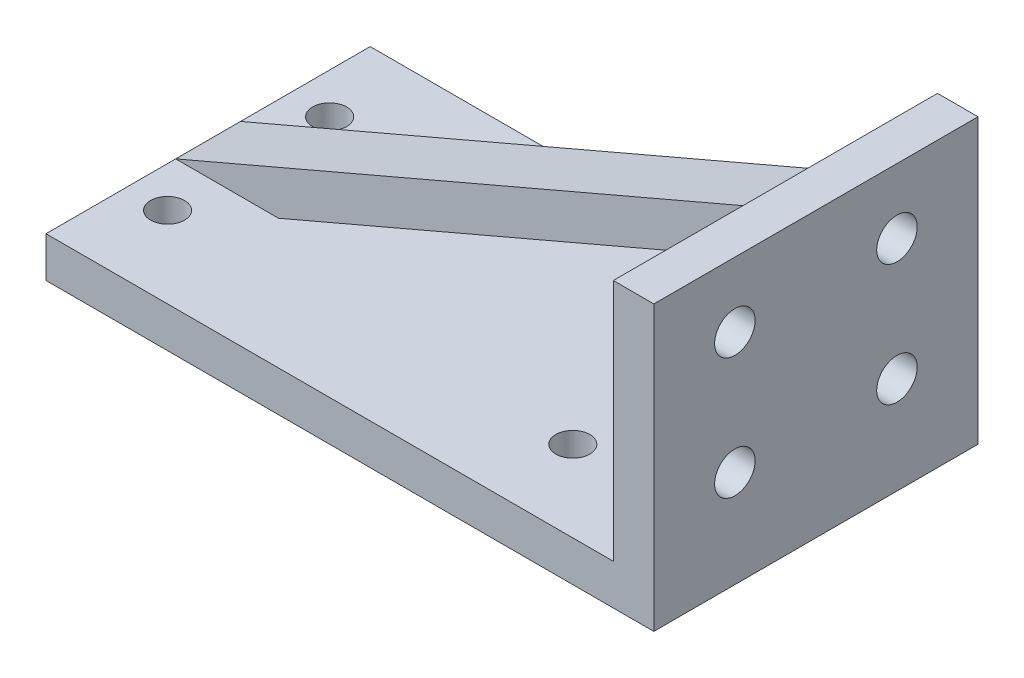
SolidWorks part; units mm, degrees
ref_plane "Front Plane" through (0, 0, 0) normal (0, 0, 1) x (1, 0, 0)
ref_plane "Top Plane" through (0, 0, 0) normal (0, 1, 0) x (1, 0, 0)
ref_plane "Right Plane" through (0, 0, 0) normal (1, 0, 0) x (0, 0, -1)
sketch "Sketch3" plane through (0, 0, 0) normal (0, 0, 1) x (1, 0, 0)
  line L0 (0, 6.35) -> (88.9, 44.45)
  line L1 (0, 0) -> (95.25, 0)
  line L2 (0, 0) -> (0, 6.35)
  line L3 (16.1201, 6.35) -> (88.9, 6.35)
  line L4 (95.25, 0) -> (95.25, 6.35)
  line L5 (95.25, 0) -> (88.9, 0)
  line L6 (95.25, 0) -> (95.25, 44.45)
  line L7 (95.25, 44.45) -> (88.9, 44.45)
  line L8 (88.9, 6.35) -> (88.9, 37.5414)
  line L9 (16.1201, 6.35) -> (88.9, 37.5414)
  line L10 (2.5014, 0.5134) -> (91.4014, 38.6134) construction
  dimension "D1" = 6.35
  dimension "D2" = 95.25
  dimension "D3" = 6.35
  dimension "D4" = 44.45
  dimension "D5" = 88.9
  dimension "D6" = 6.35
  dimension "D7" = 156.801
  dimension "D8" = 6.35
extrude "Boss-Extrude1" add sketch "Sketch3" along normal blind 50.8 contours L8 L3 L2 L1 L4 L6 L7
sketch "Sketch4" plane through (0, 0, 0) normal (0, -1, 0) x (1, 0, 0)
  line L0 (0, 50.8) -> (0, 0) construction
  line L1 (0, 0) -> (95.25, 0) construction
  line L2 (0, 50.8) -> (95.25, 50.8) construction
  circle A0 centre (6.35, 38.1) radius 2.667
  circle A1 centre (6.35, 12.7) radius 2.667
  circle A2 centre (69.85, 12.7) radius 2.667
  circle A3 centre (69.85, 38.1) radius 2.667
  dimension "D1" = 5.334
  dimension "D2" = 5.334
  dimension "D3" = 5.334
  dimension "D4" = 5.334
  dimension "D5" = 6.35
  dimension "D6" = 6.35
  dimension "D7" = 12.7
  dimension "D8" = 12.7
  dimension "D9" = 12.7
  dimension "D10" = 12.7
  dimension "D11" = 63.5
  dimension "D12" = 63.5
extrude "Cut-Extrude1" cut sketch "Sketch4" against normal through all
sketch "Sketch5" plane through (0, 0, 50.8) normal (0, 0, 1) x (1, 0, 0)
  line L1 (0, 6.35) -> (88.9, 6.35)
  line L2 (0, 6.35) -> (0, 44.45)
  line L3 (0, 44.45) -> (88.9, 44.45)
  line L4 (88.9, 6.35) -> (88.9, 44.45)
extrude "Cut-Extrude2" cut sketch "Sketch5" against normal blind 20.32
sketch "Sketch6" plane through (0, 0, 0) normal (0, 0, -1) x (-1, 0, 0)
  line L1 (-88.9, 44.45) -> (0, 44.45)
  line L2 (-88.9, 44.45) -> (-88.9, 6.35)
  line L3 (-88.9, 6.35) -> (0, 6.35)
  line L4 (0, 44.45) -> (0, 6.35)
extrude "Cut-Extrude3" cut sketch "Sketch6" against normal blind 20.32
sketch "Sketch7" plane through (95.25, 0, 0) normal (1, 0, 0) x (0, 0, -1)
  line L0 (-50.8, 0) -> (0, 0) construction
  line L1 (-50.8, 0) -> (-50.8, 44.45) construction
  line L2 (0, 0) -> (0, 44.45) construction
  circle A0 centre (-38.1, 15.24) radius 3.175
  circle A1 centre (-12.7, 15.24) radius 3.175
  circle A2 centre (-12.7, 34.29) radius 3.175
  circle A3 centre (-38.1, 34.29) radius 3.175
  dimension "D1" = 6.35
  dimension "D2" = 6.35
  dimension "D3" = 6.35
  dimension "D4" = 6.35
  dimension "D5" = 15.24
  dimension "D6" = 19.05
  dimension "D7" = 15.24
  dimension "D8" = 19.05
  dimension "D9" = 12.7
  dimension "D10" = 12.7
  dimension "D11" = 12.7
  dimension "D12" = 12.7
extrude "Cut-Extrude4" cut sketch "Sketch7" against normal through all
